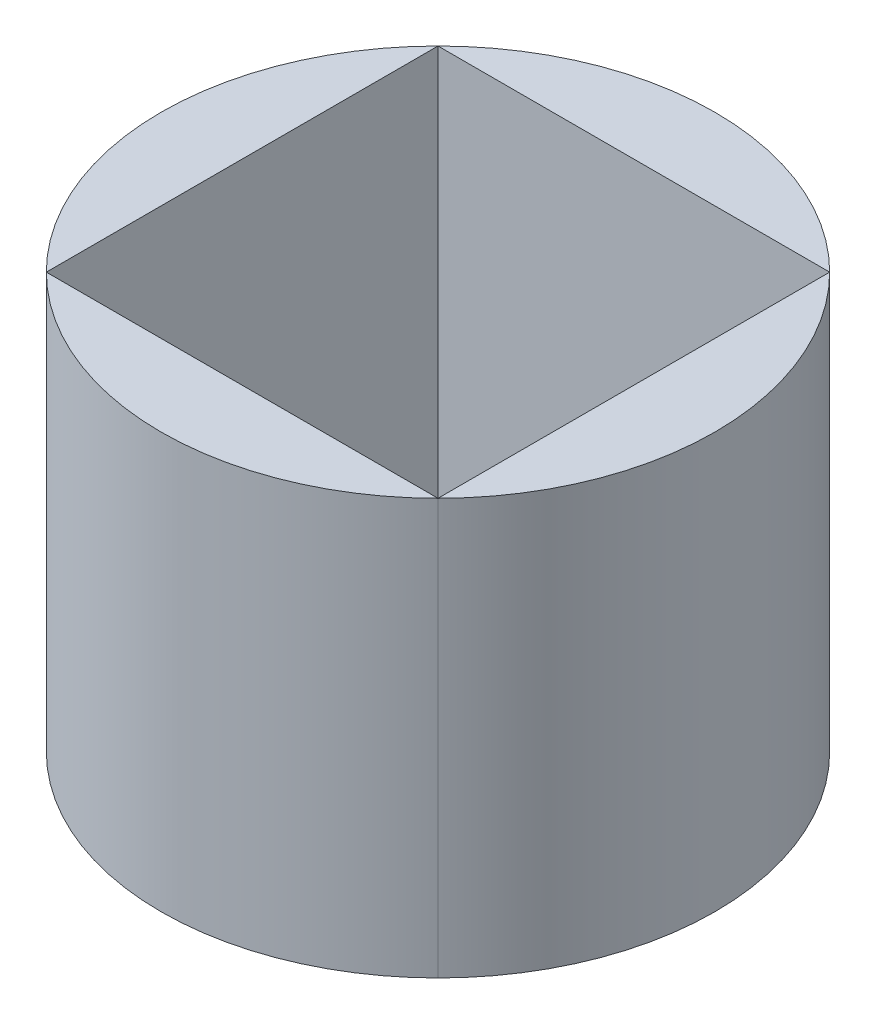
SolidWorks part; units mm, degrees
ref_plane "Front Plane" through (0, 0, 0) normal (0, 0, 1) x (1, 0, 0)
ref_plane "Top Plane" through (0, 0, 0) normal (0, 1, 0) x (1, 0, 0)
ref_plane "Right Plane" through (0, 0, 0) normal (1, 0, 0) x (0, 0, -1)
sketch "Sketch1" plane through (0, 0, 0) normal (0, 1, 0) x (1, 0, 0)
  line L1 (-1.4142, -1.4142) -> (1.4142, -1.4142)
  line L2 (-1.4142, -1.4142) -> (-1.4142, 1.4142)
  line L3 (-1.4142, 1.4142) -> (1.4142, 1.4142)
  line L4 (1.4142, -1.4142) -> (1.4142, 1.4142)
  line L5 (-1.4142, -1.4142) -> (1.4142, 1.4142) construction
  line L6 (-1.4142, 1.4142) -> (1.4142, -1.4142) construction
  circle A0 centre (0, 0) radius 2
  dimension "D1" = 4
extrude "Boss-Extrude1" add sketch "Sketch1" along normal blind 3 contours L3 A0 | L4 A0 | L1 A0 | L2 A0
